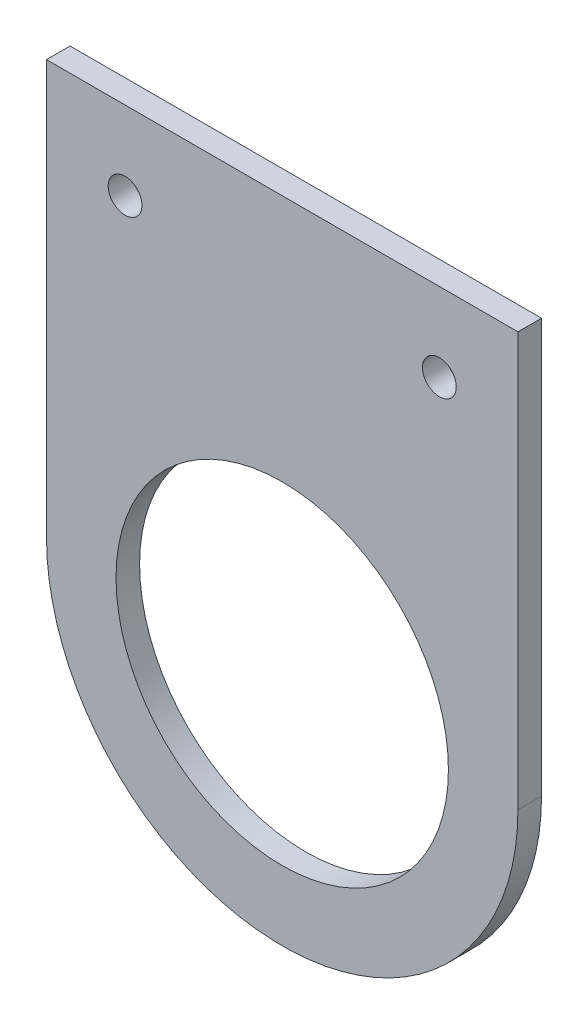
SolidWorks part; units mm, degrees
material "Thornel Mat VMA"
ref_plane "前视基准面" through (0, 0, 0) normal (0, 0, 1) x (1, 0, 0)
ref_plane "上视基准面" through (0, 0, 0) normal (0, 1, 0) x (1, 0, 0)
ref_plane "右视基准面" through (0, 0, 0) normal (1, 0, 0) x (0, 0, -1)
sketch "草图1" plane through (0, 0, 0) normal (0, 0, 1) x (1, 0, 0)
  line L0 (-30, 0) -> (-30, 52.68)
  line L1 (-30, 52.68) -> (30, 52.68)
  line L2 (30, 52.68) -> (30, 0)
  line L3 (-30, 42.68) -> (30, 42.68) construction
  circle A0 centre (0, 0) radius 21.15
  arc A1 (30, 0) -> (-30, 0) centre (0, 0) cw
  circle A2 centre (-20, 42.68) radius 2.15
  circle A3 centre (20, 42.68) radius 2.15
  point P14 (0, 0)
  dimension "D1" = 42.3
  dimension "D2" = 52.68
  dimension "D3" = 4.3
  dimension "D4" = 40
  dimension "D5" = 10
  dimension "D6" = 10
  dimension "D8" = 4.3
  dimension "D7" = 10
extrude "凸台-拉伸1" add sketch "草图1" along normal blind 3
